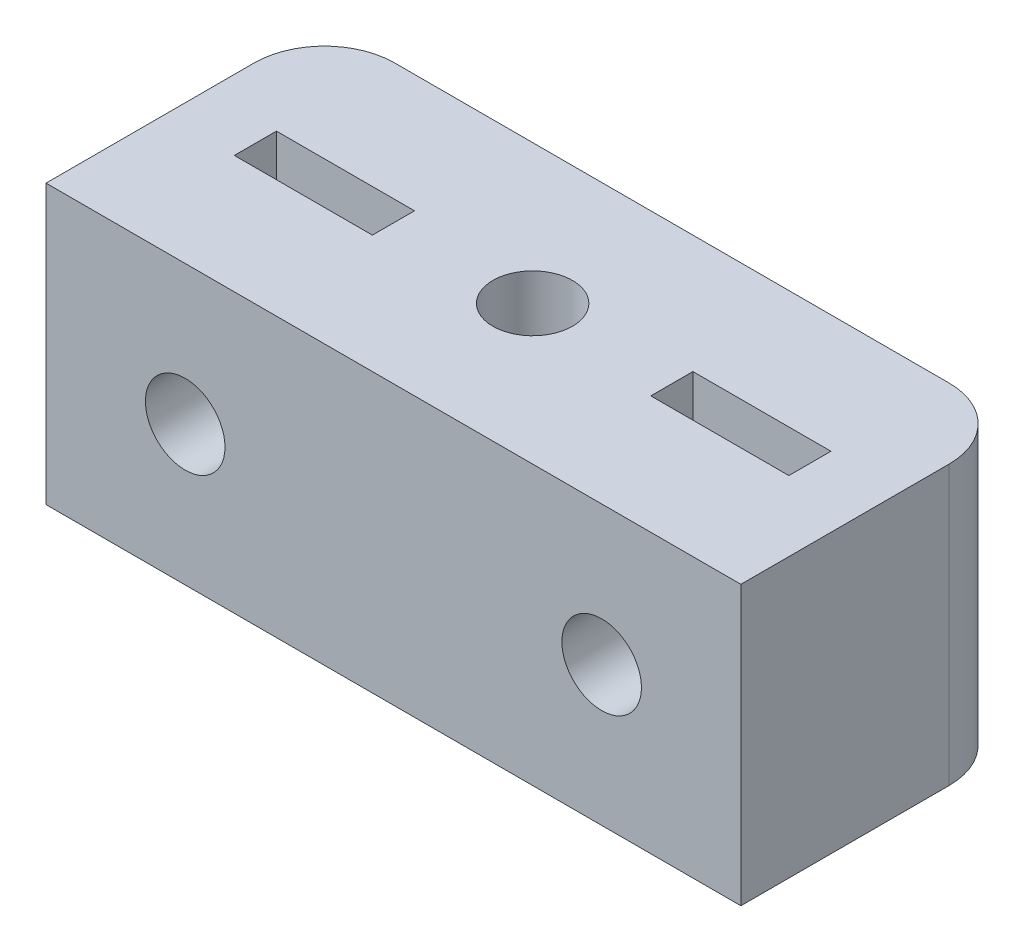
SolidWorks part; units mm, degrees
ref_plane "Front Plane" through (0, 0, 0) normal (0, 0, 1) x (1, 0, 0)
ref_plane "Top Plane" through (0, 0, 0) normal (0, 1, 0) x (1, 0, 0)
ref_plane "Right Plane" through (0, 0, 0) normal (1, 0, 0) x (0, 0, -1)
sketch "Sketch1" plane through (0, 0, 0) normal (0, 1, 0) x (1, 0, 0)
  line L1 (-14.85, -5.95) -> (14.85, -5.95)
  line L2 (-14.85, -5.95) -> (-14.85, 5.95)
  line L3 (-14.85, 5.95) -> (14.85, 5.95)
  line L4 (14.85, -5.95) -> (14.85, 5.95)
  line L5 (-14.85, -5.95) -> (14.85, 5.95) construction
  line L6 (-14.85, 5.95) -> (14.85, -5.95) construction
  point P0 (0, 0)
  dimension "D1" = 11.9
  dimension "D2" = 29.7
extrude "Boss-Extrude1" add sketch "Sketch1" along normal mid plane 11.9
sketch "Sketch2" plane through (0, 0, 5.95) normal (0, 0, 1) x (1, 0, 0)
  line L0 (-8.9, 5.95) -> (-8.9, -5.95) construction
  line L1 (-14.85, 5.95) -> (14.85, 5.95) construction
  line L3 (-14.85, 5.95) -> (-14.85, -5.95) construction
  line L4 (-14.85, -5.95) -> (14.85, -5.95) construction
  circle A0 centre (-8.9, 0) radius 1.7
  dimension "D2" = 3.4
  dimension "D1" = 5.95
extrude "Cut-Extrude1" cut sketch "Sketch2" against normal through all
sketch "Sketch3" plane through (0, 0, 0) normal (0, 0, 1) x (1, 0, 0)
  line L0 (-11.85, 2.95) -> (-11.85, 5.95)
  line L1 (-11.85, -2.95) -> (-5.95, -2.95)
  line L2 (-11.85, -2.95) -> (-11.85, 2.95)
  line L3 (-11.85, 2.95) -> (-5.95, 2.95) construction
  line L4 (-5.95, -2.95) -> (-5.95, 2.95)
  line L5 (-11.85, -2.95) -> (-5.95, 2.95) construction
  line L6 (-11.85, 2.95) -> (-5.95, -2.95) construction
  line L7 (-14.85, 5.95) -> (14.85, 5.95) construction
  line L8 (-11.85, 5.95) -> (-5.95, 5.95)
  line L9 (-5.95, 5.95) -> (-5.95, 2.95)
  circle A0 centre (-8.9, 0) radius 1.7 construction
  point P0 (-8.9, 0)
  dimension "D1" = 5.9
  dimension "D2" = 5.9
extrude "Cut-Extrude2" cut sketch "Sketch3" against normal mid plane 1.8
mirror "Mirror1" about plane through (0, 0, 0) normal (1, 0, 0) of "Cut-Extrude2", "Cut-Extrude1"
sketch "Sketch4" plane through (0, 5.95, 0) normal (0, 1, 0) x (1, 0, 0)
  circle A0 centre (0, 0) radius 1.7
  dimension "D1" = 3.4
extrude "Cut-Extrude3" cut sketch "Sketch4" against normal through all
sketch "Sketch5" plane through (0, 0, 0) normal (0, 1, 0) x (1, 0, 0)
  line L0 (-2.95, 2.95) -> (-2.95, 5.95)
  line L1 (-2.95, -2.95) -> (2.95, -2.95)
  line L2 (-2.95, -2.95) -> (-2.95, 2.95)
  line L3 (-2.95, 2.95) -> (2.95, 2.95) construction
  line L4 (2.95, -2.95) -> (2.95, 2.95)
  line L5 (-2.95, -2.95) -> (2.95, 2.95) construction
  line L6 (-2.95, 2.95) -> (2.95, -2.95) construction
  line L7 (14.85, 5.95) -> (-14.85, 5.95) construction
  line L8 (-2.95, 5.95) -> (2.95, 5.95)
  line L9 (2.95, 5.95) -> (2.95, 2.95)
  point P1 (0, 0)
  dimension "D1" = 5.9
  dimension "D2" = 5.9
extrude "Cut-Extrude4" cut sketch "Sketch5" against normal mid plane 1.8
fillet "Fillet1" radius 3 2 edges at (-14.85, 0, -5.95) (14.85, 0, -5.95)
equation "\"M3_d\"= 3.4"
equation "\"M3_nut_m\"= 1.8"
equation "\"M3_nut_s\"= 5.9"
equation "\"t\"= 3"
equation "\"D1@Sketch1\"=\"M3_nut_s\" + 2 * \"t\""
equation "\"D2@Sketch1\"=3 * \"M3_nut_s\" + 2 * \"t\" + 2 * \"t\""
equation "\"D1@Boss-Extrude1\"=\"M3_nut_s\" + 2 * \"t\""
equation "\"D1@Sketch2\"=\"t\" + \"M3_nut_s\" / 2 "
equation "\"D2@Sketch2\"=\"M3_d\""
equation "\"D1@Sketch3\"=\"M3_nut_s\""
equation "\"D2@Sketch3\"=\"M3_nut_s\""
equation "\"D1@Cut-Extrude2\"=\"M3_nut_m\""
equation "\"D1@Sketch4\"=\"M3_d\""
equation "\"D1@Sketch5\"=\"M3_nut_s\""
equation "\"D2@Sketch5\"=\"M3_nut_s\""
equation "\"D1@Cut-Extrude4\"=\"M3_nut_m\""
equation "\"D1@Fillet1\"=\"t\""
